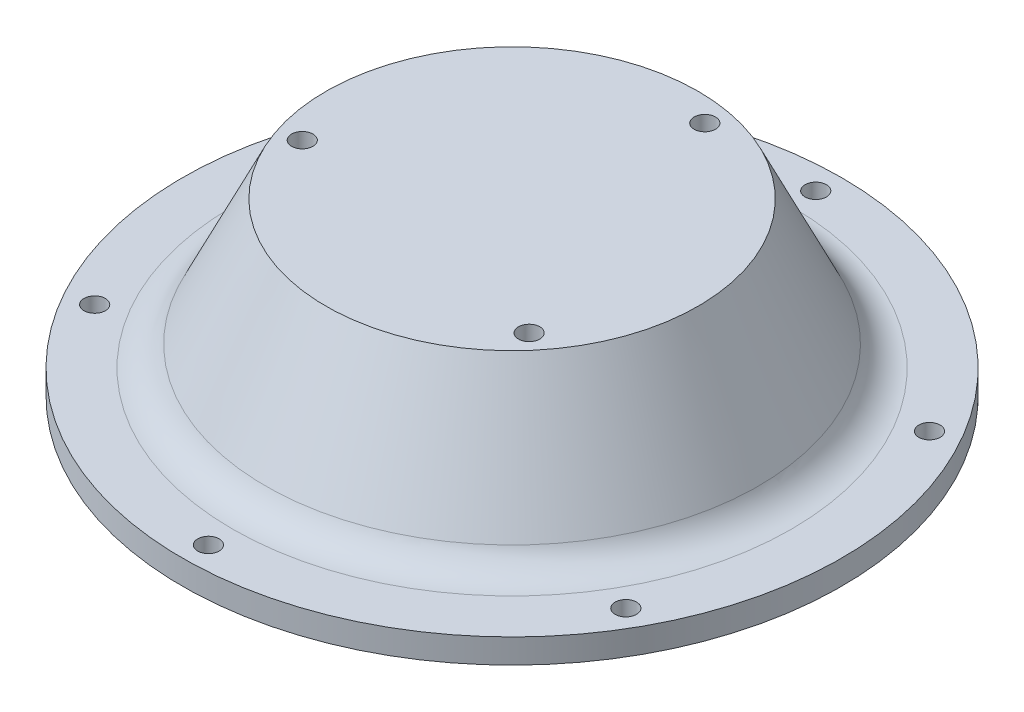
SolidWorks part; units mm, degrees
ref_plane "Front Plane" through (0, 0, 0) normal (0, 0, 1) x (1, 0, 0)
ref_plane "Top Plane" through (0, 0, 0) normal (0, 1, 0) x (1, 0, 0)
ref_plane "Right Plane" through (0, 0, 0) normal (1, 0, 0) x (0, 0, -1)
sketch "Sketch2" plane through (0, 0, 0) normal (0, 0, 1) x (1, 0, 0)
  line L7 (0, 0) -> (42, 0)
  line L8 (42, 0) -> (42, 24)
  line L9 (42, 24) -> (11.5, 24)
  line L10 (11.5, 24) -> (0, 0)
  dimension "D1" = 42
  dimension "D2" = 24
  dimension "D3" = 30.5
revolve "Revolve2" add sketch "Sketch2" angle 360 about L8
sketch "Sketch4" plane through (0, 0, 0) normal (0, -1, 0) x (1, 0, 0)
  circle A0 centre (42, 0) radius 54
  circle A1 centre (42, 0) radius 42 construction
extrude "Boss-Extrude1" add sketch "Sketch4" along normal blind 4
fillet "Fillet1" radius 6 1 edges at (42, 0, -42)
sketch "Sketch7" plane through (0, 0, 0) normal (0, 1, 0) x (1, 0, 0)
  circle A0 centre (42.2469, -49.9994) radius 1.75
  circle A1 centre (-1.1773, -25.2135) radius 1.75
  circle A2 centre (-1.4242, 24.7858) radius 1.75
  circle A3 centre (41.7531, 49.9994) radius 1.75
  circle A4 centre (85.1773, 25.2135) radius 1.75
  circle A5 centre (85.4242, -24.7858) radius 1.75
  point P15 (42, 0)
  dimension "D1" = 6
sketch "Sketch9" plane through (0, 24, 0) normal (0, 1, 0) x (1, 0, 0)
  circle A2 centre (47.0595, 26.5217) radius 1.75
  circle A3 centre (62.4387, -17.6425) radius 1.75
  circle A4 centre (16.5018, -8.8792) radius 1.75
  point P13 (42, 0)
  dimension "D1" = 3
extrude "Cut-Extrude2" cut sketch "Sketch9" against normal blind 50 contours A4 | A3 | A2
extrude "Cut-Extrude3" cut sketch "Sketch7" against normal blind 50
